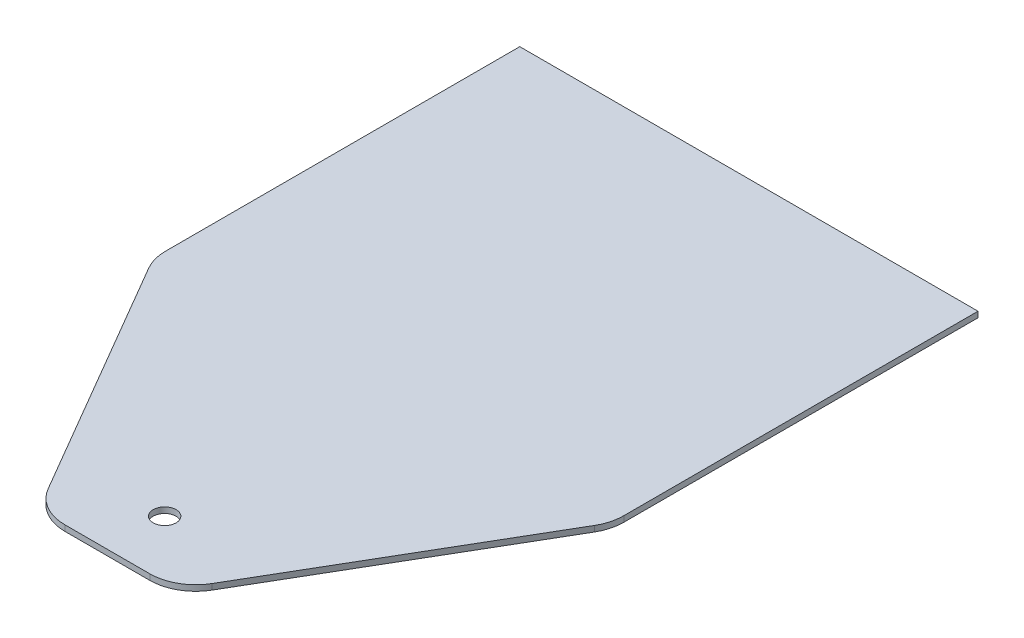
SolidWorks part; units mm, degrees
ref_plane "Front Plane" through (0, 0, 0) normal (0, 0, 1) x (1, 0, 0)
ref_plane "Top Plane" through (0, 0, 0) normal (0, 1, 0) x (1, 0, 0)
ref_plane "Right Plane" through (0, 0, 0) normal (1, 0, 0) x (0, 0, -1)
sketch "Sketch1" plane through (0, 0, 0) normal (0, 1, 0) x (1, 0, 0)
  line L0 (-63.5, 0) -> (63.5, 0)
  line L1 (-63.5, 0) -> (-63.5, -101.6)
  line L2 (-63.5, -101.6) -> (-19.05, -177.8)
  line L3 (-19.05, -177.8) -> (19.05, -177.8)
  line L4 (19.05, -177.8) -> (63.5, -101.6)
  line L5 (63.5, -101.6) -> (63.5, 0)
  point P4 (0, 0)
  point P8 (0, -177.8)
  point P10 (-29.3669, -145.1906)
  dimension "D1" = 127
  dimension "D2" = 101.6
  dimension "D3" = 177.8
  dimension "D4" = 38.1
extrude "Boss-Extrude1" add sketch "Sketch1" along normal mid plane 1.5875
fillet "Fillet1" radius 12.7 4 edges at (63.5, 0, 101.6) (-63.5, 0, 101.6) (-19.05, 0, 177.8) (19.05, 0, 177.8)
sketch "Sketch2" plane through (0, 0.7937, 0) normal (0, 1, 0) x (1, 0, 0)
  line L0 (-11.7555, -177.8) -> (11.7555, -177.8) construction
  circle A0 centre (0, -161.925) radius 3.175
  point P4 (-10.6213, -165.1)
  dimension "D1" = 6.35
  dimension "D2" = 15.875
extrude "Cut-Extrude1" cut sketch "Sketch2" against normal up to next
